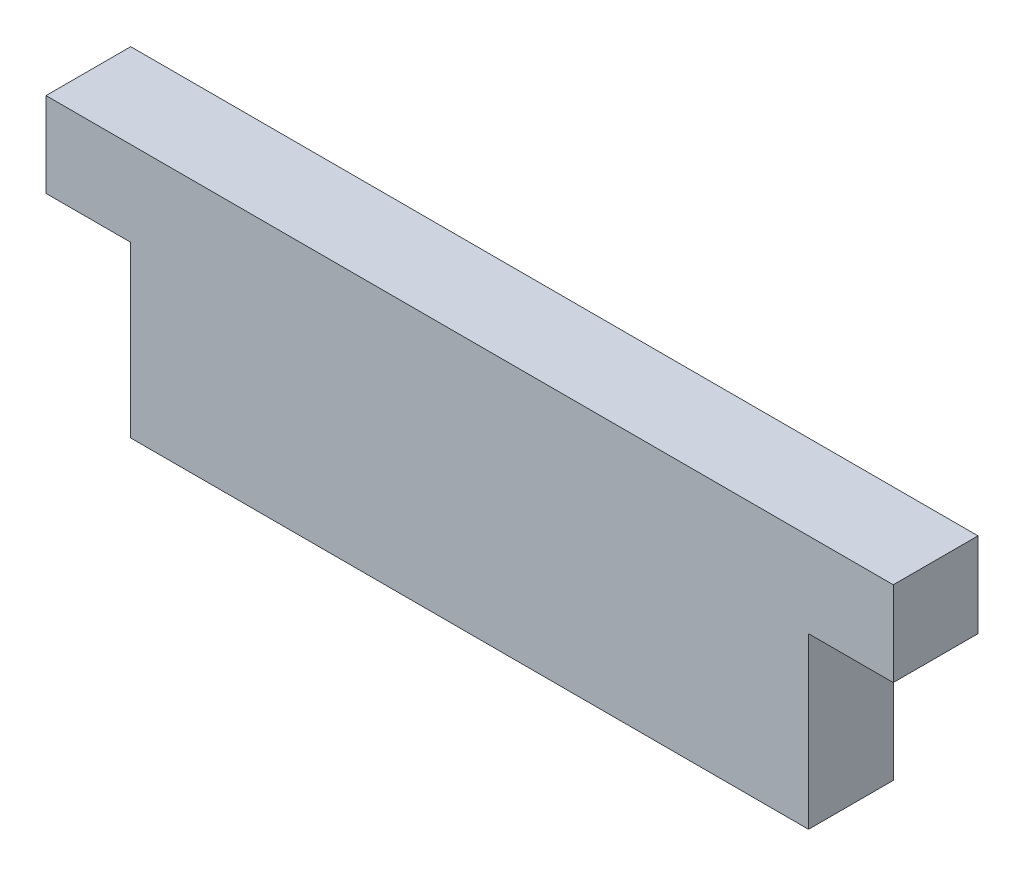
SolidWorks part; units mm, degrees
ref_plane "Front Plane" through (0, 0, 0) normal (0, 0, 1) x (1, 0, 0)
ref_plane "Top Plane" through (0, 0, 0) normal (0, 1, 0) x (1, 0, 0)
ref_plane "Right Plane" through (0, 0, 0) normal (1, 0, 0) x (0, 0, -1)
sketch "Sketch1" plane through (0, 0, 0) normal (0, 0, 1) x (1, 0, 0)
  line L1 (0, 0) -> (-40, 0)
  line L2 (0, 0) -> (0, -10)
  line L3 (0, -10) -> (-40, -10)
  line L4 (-40, 0) -> (-40, -10)
  line L5 (-45, 0) -> (5, 0)
  line L6 (-45, 0) -> (-45, 5)
  line L7 (-45, 5) -> (5, 5)
  line L8 (5, 0) -> (5, 5)
  dimension "D1" = 40
  dimension "D2" = 10
  dimension "D3" = 50
  dimension "D4" = 5
  dimension "D5" = 5
extrude "Boss-Extrude1" add sketch "Sketch1" along normal blind 5 contours L1 L4 L3 L2 | L5 L8 L7 L6 L1
